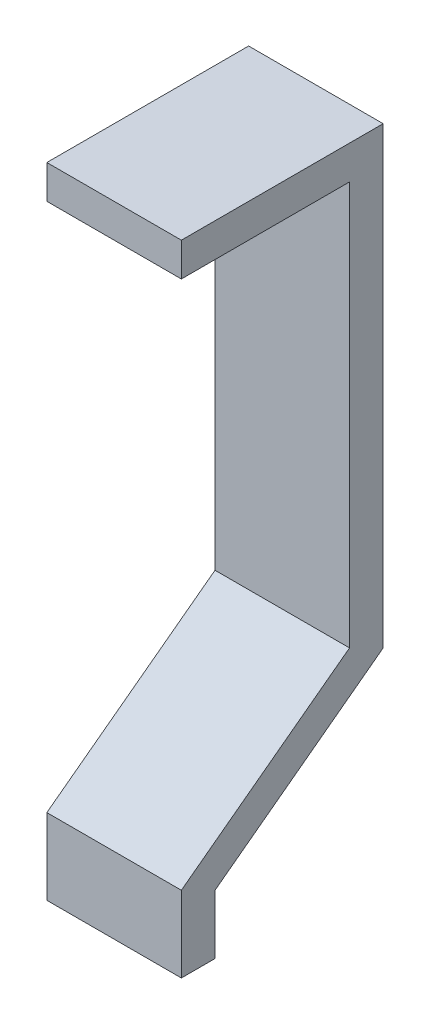
SolidWorks part; units mm, degrees
ref_plane "Front Plane" through (0, 0, 0) normal (0, 0, 1) x (1, 0, 0)
ref_plane "Top Plane" through (0, 0, 0) normal (0, 1, 0) x (1, 0, 0)
ref_plane "Right Plane" through (0, 0, 0) normal (1, 0, 0) x (0, 0, -1)
sketch "Sketch1" plane through (0, 0, 0) normal (1, 0, 0) x (0, 0, -1)
  line L0 (-10, 190) -> (50, 190)
  line L1 (50, 190) -> (50, 54.9921)
  line L2 (50, 54.9921) -> (0, 17.5907)
  line L3 (0, 17.5907) -> (0, 0)
  line L4 (0, 0) -> (-10, 0)
  line L5 (-10, 0) -> (-10, 22.5986)
  line L6 (-10, 22.5986) -> (40, 60)
  line L7 (40, 60) -> (40, 180)
  line L8 (40, 180) -> (-10, 180)
  line L9 (-10, 190) -> (-10, 180)
  point P2 (0, 0)
  point P12 (-10, -122.0101)
  point P13 (-10, -111.0276)
  point P14 (-10, 0)
  point P15 (0, 0)
  point P16 (0, 0)
  point P17 (0, 0)
  point P18 (0, 30.8059)
  point P19 (0, 26.2132)
  point P20 (50, 54.1303)
  point P21 (-10, 22.5986)
  dimension "D1" = 190
  dimension "D2" = 50
  dimension "D3" = 10
  dimension "D4" = 10
  dimension "D5" = 10
  dimension "D6" = 10
  dimension "D7" = 120
extrude "Boss-Extrude1" add sketch "Sketch1" along normal blind 40
